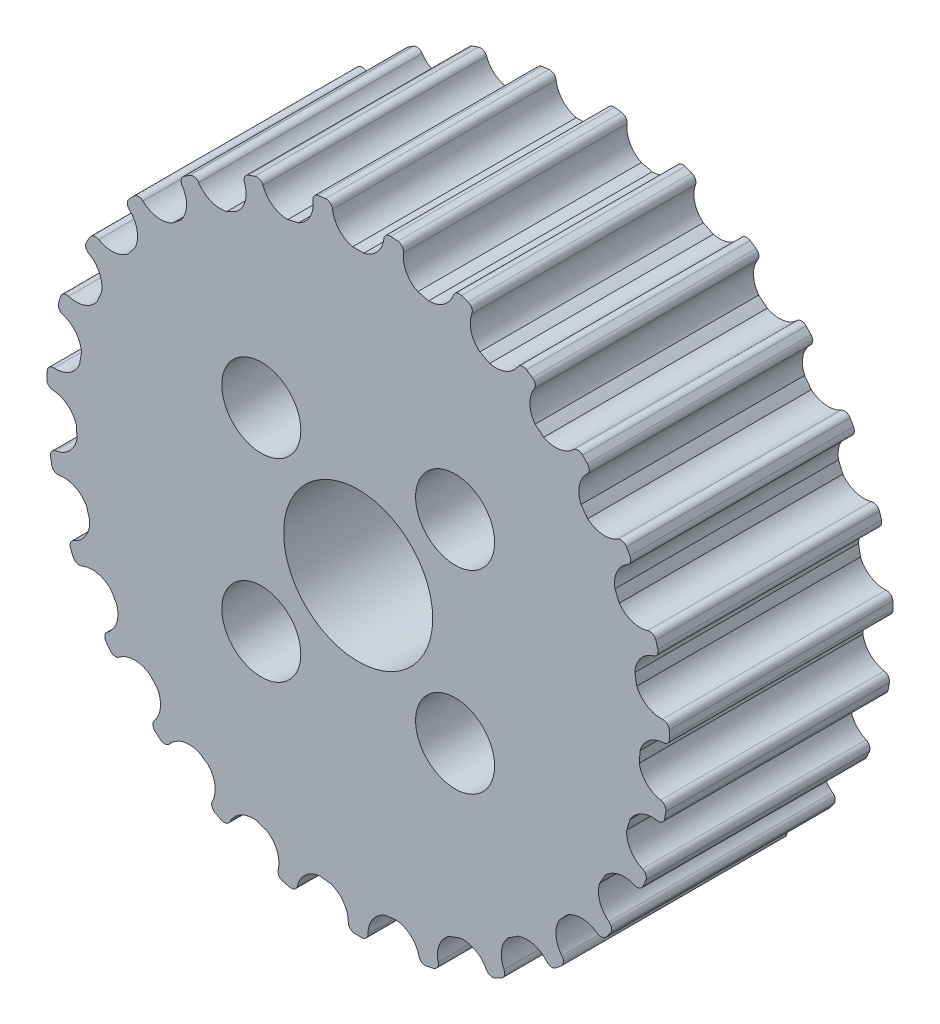
SolidWorks part; units mm, degrees
ref_plane "Front Plane" through (0, 0, 0) normal (0, 0, 1) x (1, 0, 0)
ref_plane "Top Plane" through (0, 0, 0) normal (0, 1, 0) x (1, 0, 0)
ref_plane "Right Plane" through (0, 0, 0) normal (1, 0, 0) x (0, 0, -1)
ref_plane "Plane1" through (0, 0, 7.5) normal (0, 0, 1) x (1, 0, 0)
sketch "Sketch1" plane through (0, 0, 7.5) normal (0, 0, 1) x (1, 0, 0)
  arc A0 (-2.1927, 20.7989) -> (-2.663, 20.7439) centre (0, 0) ccw
  arc A1 (-2.663, 20.7439) -> (-3.0351, 20.266) centre (-2.6082, 20.3174) ccw
  arc A2 (-3.0351, 20.266) -> (-3.9982, 18.4886) centre (-4.7708, 20.0568) cw
  arc A3 (-3.9982, 18.4886) -> (-4.7247, 18.3164) centre (0, 0) ccw
  arc A4 (-4.7247, 18.3164) -> (-6.3831, 19.4725) centre (-4.7381, 20.0646) cw
  arc A5 (-6.3831, 19.4725) -> (-6.9301, 19.7326) centre (-6.7876, 19.3269) ccw
  arc A6 (-6.9301, 19.7326) -> (-7.3751, 19.5706) centre (0, 0) ccw
  arc A7 (-7.3751, 19.5706) -> (-7.627, 19.0198) centre (-7.2234, 19.1683) ccw
  arc A8 (-7.627, 19.0198) -> (-8.1542, 17.0682) centre (-9.2676, 18.416) cw
  arc A9 (-8.1542, 17.0682) -> (-8.8214, 16.7331) centre (0, 0) ccw
  arc A10 (-8.8214, 16.7331) -> (-10.7017, 17.4756) centre (-9.2376, 18.431) cw
  arc A11 (-10.7017, 17.4756) -> (-11.294, 17.6025) centre (-11.0618, 17.2406) ccw
  arc A12 (-11.294, 17.6025) -> (-11.6896, 17.3423) centre (0, 0) ccw
  arc A13 (-11.6896, 17.3423) -> (-11.8077, 16.7482) centre (-11.4492, 16.9857) ccw
  arc A14 (-11.8077, 16.7482) -> (-11.8706, 14.7276) centre (-13.2649, 15.7823) cw
  arc A15 (-11.8706, 14.7276) -> (-12.4425, 14.2477) centre (0, 0) ccw
  arc A16 (-12.4425, 14.2477) -> (-14.4433, 14.5366) centre (-13.2391, 15.8039) cw
  arc A17 (-14.4433, 14.5366) -> (-15.049, 14.5235) centre (-14.7395, 14.2248) ccw
  arc A18 (-15.049, 14.5235) -> (-15.3739, 14.179) centre (0, 0) ccw
  arc A19 (-15.3739, 14.179) -> (-15.3518, 13.5737) centre (-15.0578, 13.8875) ccw
  arc A20 (-15.3518, 13.5737) -> (-14.947, 11.5931) centre (-16.5469, 12.2978) cw
  arc A21 (-14.947, 11.5931) -> (-15.3929, 10.9942) centre (0, 0) ccw
  arc A22 (-15.3929, 10.9942) -> (-17.4064, 10.8139) centre (-16.5269, 12.3248) cw
  arc A23 (-17.4064, 10.8139) -> (-17.9926, 10.6614) centre (-17.6227, 10.4422) ccw
  arc A24 (-17.9926, 10.6614) -> (-18.2294, 10.2514) centre (0, 0) ccw
  arc A25 (-18.2294, 10.2514) -> (-18.0683, 9.6674) centre (-17.8546, 10.0406) ccw
  arc A26 (-18.0683, 9.6674) -> (-17.2177, 7.8335) centre (-18.937, 8.1503) cw
  arc A27 (-17.2177, 7.8335) -> (-17.5134, 7.148) centre (0, 0) ccw
  arc A28 (-17.5134, 7.148) -> (-19.431, 6.5082) centre (-18.9237, 8.1812) cw
  arc A29 (-19.431, 6.5082) -> (-19.9664, 6.2247) centre (-19.5558, 6.0967) ccw
  arc A30 (-19.9664, 6.2247) -> (-20.1022, 5.7711) centre (0, 0) ccw
  arc A31 (-20.1022, 5.7711) -> (-19.8107, 5.24) centre (-19.6889, 5.6524) ccw
  arc A32 (-19.8107, 5.24) -> (-18.5601, 3.6517) centre (-20.3061, 3.5635) cw
  arc A33 (-18.5601, 3.6517) -> (-18.6898, 2.9164) centre (0, 0) ccw
  arc A34 (-18.6898, 2.9164) -> (-20.4082, 1.8516) centre (-20.3003, 3.5966) cw
  arc A35 (-20.4082, 1.8516) -> (-20.8637, 1.4523) centre (-20.4347, 1.4225) ccw
  arc A36 (-20.8637, 1.4523) -> (-20.8912, 0.9796) centre (0, 0) ccw
  arc A37 (-20.8912, 0.9796) -> (-20.4851, 0.5301) centre (-20.4617, 0.9595) ccw
  arc A38 (-20.4851, 0.5301) -> (-18.902, -0.727) centre (-20.5806, -1.2155) cw
  arc A39 (-18.902, -0.727) -> (-18.8586, -1.4723) centre (0, 0) ccw
  arc A40 (-18.8586, -1.4723) -> (-20.2851, -2.9047) centre (-20.5825, -1.182) cw
  arc A41 (-20.2851, -2.9047) -> (-20.6362, -3.3983) centre (-20.2119, -3.3284) ccw
  arc A42 (-20.6362, -3.3983) -> (-20.554, -3.8646) centre (0, 0) ccw
  arc A43 (-20.554, -3.8646) -> (-20.0552, -4.2084) centre (-20.1314, -3.7852) ccw
  arc A44 (-20.0552, -4.2084) -> (-18.2248, -5.0665) centre (-19.7455, -5.929) cw
  arc A45 (-18.2248, -5.0665) -> (-18.0107, -5.7817) centre (0, 0) ccw
  arc A46 (-18.0107, -5.7817) -> (-19.0684, -7.5045) centre (-19.7551, -5.8968) cw
  arc A47 (-19.0684, -7.5045) -> (-19.2963, -8.0657) centre (-18.8995, -7.8999) ccw
  arc A48 (-19.2963, -8.0657) -> (-19.1087, -8.5005) centre (0, 0) ccw
  arc A49 (-19.1087, -8.5005) -> (-18.5441, -8.72) centre (-18.7158, -8.3258) ccw
  arc A50 (-18.5441, -8.72) -> (-16.5652, -9.1328) centre (-17.8459, -10.3228) cw
  arc A51 (-16.5652, -9.1328) -> (-16.1918, -9.7794) centre (0, 0) ccw
  arc A52 (-16.1918, -9.7794) -> (-16.8238, -11.6997) centre (-17.8627, -10.2937) cw
  arc A53 (-16.8238, -11.6997) -> (-16.916, -12.2984) centre (-16.5682, -12.0455) ccw
  arc A54 (-16.916, -12.2984) -> (-16.6333, -12.6782) centre (0, 0) ccw
  arc A55 (-16.6333, -12.6782) -> (-16.0333, -12.7615) centre (-16.2913, -12.4175) ccw
  arc A56 (-16.0333, -12.7615) -> (-14.0125, -12.7068) centre (-14.9843, -14.1601) cw
  arc A57 (-14.0125, -12.7068) -> (-13.5001, -13.2499) centre (0, 0) ccw
  arc A58 (-13.5001, -13.2499) -> (-13.6722, -15.2641) centre (-15.0074, -14.1356) cw
  arc A59 (-13.6722, -15.2641) -> (-13.6239, -15.868) centre (-13.3438, -15.5417) ccw
  arc A60 (-13.6239, -15.868) -> (-13.2611, -16.1723) centre (0, 0) ccw
  arc A61 (-13.2611, -16.1723) -> (-12.6581, -16.115) centre (-12.9885, -15.8398) ccw
  arc A62 (-12.6581, -16.115) -> (-10.7044, -15.5958) centre (-11.3149, -17.234) cw
  arc A63 (-10.7044, -15.5958) -> (-10.0806, -16.0061) centre (0, 0) ccw
  arc A64 (-10.0806, -16.0061) -> (-9.7835, -18.0057) centre (-11.3429, -17.2155) cw
  arc A65 (-9.7835, -18.0057) -> (-9.5972, -18.5821) centre (-9.3999, -18.2001) ccw
  arc A66 (-9.5972, -18.5821) -> (-9.1741, -18.7946) centre (0, 0) ccw
  arc A67 (-9.1741, -18.7946) -> (-8.6005, -18.5998) centre (-8.9855, -18.4082) ccw
  arc A68 (-8.6005, -18.5998) -> (-6.8192, -17.644) centre (-7.0354, -19.3788) cw
  arc A69 (-6.8192, -17.644) -> (-6.1176, -17.8994) centre (0, 0) ccw
  arc A70 (-6.1176, -17.8994) -> (-5.3674, -19.7766) centre (-7.067, -19.3674) cw
  arc A71 (-5.3674, -19.7766) -> (-5.0532, -20.2945) centre (-4.9493, -19.8772) ccw
  arc A72 (-5.0532, -20.2945) -> (-4.5925, -20.4037) centre (0, 0) ccw
  arc A73 (-4.5925, -20.4037) -> (-4.0793, -20.0819) centre (-4.498, -19.9842) ccw
  arc A74 (-4.0793, -20.0819) -> (-2.5664, -18.7411) centre (-2.3767, -20.479) cw
  arc A75 (-2.5664, -18.7411) -> (-1.8248, -18.8277) centre (0, 0) ccw
  arc A76 (-1.8248, -18.8277) -> (-0.6619, -20.4813) centre (-2.4101, -20.4751) cw
  arc A77 (-0.6619, -20.4813) -> (-0.2368, -20.9128) centre (-0.2319, -20.4828) ccw
  arc A78 (-0.2368, -20.9128) -> (0.2368, -20.9128) centre (0, 0) ccw
  arc A79 (0.2368, -20.9128) -> (0.6619, -20.4813) centre (0.2319, -20.4828) ccw
  arc A80 (0.6619, -20.4813) -> (1.8248, -18.8277) centre (2.4101, -20.4751) cw
  arc A81 (1.8248, -18.8277) -> (2.5664, -18.7411) centre (0, 0) ccw
  arc A82 (2.5664, -18.7411) -> (4.0793, -20.0819) centre (2.3767, -20.479) cw
  arc A83 (4.0793, -20.0819) -> (4.5925, -20.4037) centre (4.498, -19.9842) ccw
  arc A84 (4.5925, -20.4037) -> (5.0532, -20.2945) centre (0, 0) ccw
  arc A85 (5.0532, -20.2945) -> (5.3674, -19.7766) centre (4.9493, -19.8772) ccw
  arc A86 (5.3674, -19.7766) -> (6.1176, -17.8994) centre (7.067, -19.3674) cw
  arc A87 (6.1176, -17.8994) -> (6.8192, -17.644) centre (0, 0) ccw
  arc A88 (6.8192, -17.644) -> (8.6005, -18.5998) centre (7.0354, -19.3788) cw
  arc A89 (8.6005, -18.5998) -> (9.1741, -18.7946) centre (8.9855, -18.4082) ccw
  arc A90 (9.1741, -18.7946) -> (9.5972, -18.5821) centre (0, 0) ccw
  arc A91 (9.5972, -18.5821) -> (9.7835, -18.0057) centre (9.3999, -18.2001) ccw
  arc A92 (9.7835, -18.0057) -> (10.0806, -16.0061) centre (11.3429, -17.2155) cw
  arc A93 (10.0806, -16.0061) -> (10.7044, -15.5958) centre (0, 0) ccw
  arc A94 (10.7044, -15.5958) -> (12.6581, -16.115) centre (11.3149, -17.234) cw
  arc A95 (12.6581, -16.115) -> (13.2611, -16.1723) centre (12.9885, -15.8398) ccw
  arc A96 (13.2611, -16.1723) -> (13.6239, -15.868) centre (0, 0) ccw
  arc A97 (13.6239, -15.868) -> (13.6722, -15.2641) centre (13.3438, -15.5417) ccw
  arc A98 (13.6722, -15.2641) -> (13.5001, -13.2499) centre (15.0074, -14.1356) cw
  arc A99 (13.5001, -13.2499) -> (14.0125, -12.7068) centre (0, 0) ccw
  arc A100 (14.0125, -12.7068) -> (16.0333, -12.7615) centre (14.9843, -14.1601) cw
  arc A101 (16.0333, -12.7615) -> (16.6333, -12.6782) centre (16.2913, -12.4175) ccw
  arc A102 (16.6333, -12.6782) -> (16.916, -12.2984) centre (0, 0) ccw
  arc A103 (16.916, -12.2984) -> (16.8238, -11.6997) centre (16.5682, -12.0455) ccw
  arc A104 (16.8238, -11.6997) -> (16.1918, -9.7794) centre (17.8627, -10.2937) cw
  arc A105 (16.1918, -9.7794) -> (16.5652, -9.1328) centre (0, 0) ccw
  arc A106 (16.5652, -9.1328) -> (18.5441, -8.72) centre (17.8459, -10.3228) cw
  arc A107 (18.5441, -8.72) -> (19.1087, -8.5005) centre (18.7158, -8.3258) ccw
  arc A108 (19.1087, -8.5005) -> (19.2963, -8.0657) centre (0, 0) ccw
  arc A109 (19.2963, -8.0657) -> (19.0684, -7.5045) centre (18.8995, -7.8999) ccw
  arc A110 (19.0684, -7.5045) -> (18.0107, -5.7817) centre (19.7551, -5.8968) cw
  arc A111 (18.0107, -5.7817) -> (18.2248, -5.0665) centre (0, 0) ccw
  arc A112 (18.2248, -5.0665) -> (20.0552, -4.2084) centre (19.7455, -5.929) cw
  arc A113 (20.0552, -4.2084) -> (20.554, -3.8646) centre (20.1314, -3.7852) ccw
  arc A114 (20.554, -3.8646) -> (20.6362, -3.3983) centre (0, 0) ccw
  arc A115 (20.6362, -3.3983) -> (20.2851, -2.9047) centre (20.2119, -3.3284) ccw
  arc A116 (20.2851, -2.9047) -> (18.8586, -1.4723) centre (20.5825, -1.182) cw
  arc A117 (18.8586, -1.4723) -> (18.902, -0.727) centre (0, 0) ccw
  arc A118 (18.902, -0.727) -> (20.4851, 0.5301) centre (20.5806, -1.2155) cw
  arc A119 (20.4851, 0.5301) -> (20.8912, 0.9796) centre (20.4617, 0.9595) ccw
  arc A120 (20.8912, 0.9796) -> (20.8637, 1.4523) centre (0, 0) ccw
  arc A121 (20.8637, 1.4523) -> (20.4082, 1.8516) centre (20.4347, 1.4225) ccw
  arc A122 (20.4082, 1.8516) -> (18.6898, 2.9164) centre (20.3003, 3.5966) cw
  arc A123 (18.6898, 2.9164) -> (18.5601, 3.6517) centre (0, 0) ccw
  arc A124 (18.5601, 3.6517) -> (19.8107, 5.24) centre (20.3061, 3.5635) cw
  arc A125 (19.8107, 5.24) -> (20.1022, 5.7711) centre (19.6889, 5.6524) ccw
  arc A126 (20.1022, 5.7711) -> (19.9664, 6.2247) centre (0, 0) ccw
  arc A127 (19.9664, 6.2247) -> (19.431, 6.5082) centre (19.5558, 6.0967) ccw
  arc A128 (19.431, 6.5082) -> (17.5134, 7.148) centre (18.9237, 8.1812) cw
  arc A129 (17.5134, 7.148) -> (17.2177, 7.8335) centre (0, 0) ccw
  arc A130 (17.2177, 7.8335) -> (18.0683, 9.6674) centre (18.937, 8.1503) cw
  arc A131 (18.0683, 9.6674) -> (18.2294, 10.2514) centre (17.8546, 10.0406) ccw
  arc A132 (18.2294, 10.2514) -> (17.9926, 10.6614) centre (0, 0) ccw
  arc A133 (17.9926, 10.6614) -> (17.4064, 10.8139) centre (17.6227, 10.4422) ccw
  arc A134 (17.4064, 10.8139) -> (15.3929, 10.9942) centre (16.5269, 12.3248) cw
  arc A135 (15.3929, 10.9942) -> (14.947, 11.5931) centre (0, 0) ccw
  arc A136 (14.947, 11.5931) -> (15.3518, 13.5737) centre (16.5469, 12.2978) cw
  arc A137 (15.3518, 13.5737) -> (15.3739, 14.179) centre (15.0578, 13.8875) ccw
  arc A138 (15.3739, 14.179) -> (15.049, 14.5235) centre (0, 0) ccw
  arc A139 (15.049, 14.5235) -> (14.4433, 14.5366) centre (14.7395, 14.2248) ccw
  arc A140 (14.4433, 14.5366) -> (12.4425, 14.2477) centre (13.2391, 15.8039) cw
  arc A141 (12.4425, 14.2477) -> (11.8706, 14.7276) centre (0, 0) ccw
  arc A142 (11.8706, 14.7276) -> (11.8077, 16.7482) centre (13.2649, 15.7823) cw
  arc A143 (11.8077, 16.7482) -> (11.6896, 17.3423) centre (11.4492, 16.9857) ccw
  arc A144 (11.6896, 17.3423) -> (11.294, 17.6025) centre (0, 0) ccw
  arc A145 (11.294, 17.6025) -> (10.7017, 17.4756) centre (11.0618, 17.2406) ccw
  arc A146 (10.7017, 17.4756) -> (8.8214, 16.7331) centre (9.2376, 18.431) cw
  arc A147 (8.8214, 16.7331) -> (8.1542, 17.0682) centre (0, 0) ccw
  arc A148 (8.1542, 17.0682) -> (7.627, 19.0198) centre (9.2676, 18.416) cw
  arc A149 (7.627, 19.0198) -> (7.3751, 19.5706) centre (7.2234, 19.1683) ccw
  arc A150 (7.3751, 19.5706) -> (6.9301, 19.7326) centre (0, 0) ccw
  arc A151 (6.9301, 19.7326) -> (6.3831, 19.4725) centre (6.7876, 19.3269) ccw
  arc A152 (6.3831, 19.4725) -> (4.7247, 18.3164) centre (4.7381, 20.0646) cw
  arc A153 (4.7247, 18.3164) -> (3.9982, 18.4886) centre (0, 0) ccw
  arc A154 (3.9982, 18.4886) -> (3.0351, 20.266) centre (4.7708, 20.0568) cw
  arc A155 (3.0351, 20.266) -> (2.663, 20.7439) centre (2.6082, 20.3174) ccw
  arc A156 (2.663, 20.7439) -> (2.1927, 20.7989) centre (0, 0) ccw
  arc A157 (2.1927, 20.7989) -> (1.7203, 20.4197) centre (2.1476, 20.3713) ccw
  arc A158 (1.7203, 20.4197) -> (0.3733, 18.9123) centre (-0.0168, 20.6164) cw
  arc A159 (0.3733, 18.9123) -> (-0.3733, 18.9123) centre (0, 0) ccw
  arc A160 (-0.3733, 18.9123) -> (-1.7203, 20.4197) centre (0.0168, 20.6164) cw
  arc A161 (-1.7203, 20.4197) -> (-2.1927, 20.7989) centre (-2.1476, 20.3713) ccw
extrude "Boss-Extrude1" add sketch "Sketch1" against normal blind 15
sketch "Sketch2" plane through (0, 0, 7.5) normal (0, 0, 1) x (1, 0, 0)
  line L1 (-6.5, -6.5) -> (6.5, -6.5) construction
  line L2 (-6.5, -6.5) -> (-6.5, 6.5) construction
  line L3 (-6.5, 6.5) -> (6.5, 6.5) construction
  line L4 (6.5, -6.5) -> (6.5, 6.5) construction
  line L5 (-6.5, -6.5) -> (6.5, 6.5) construction
  line L6 (-6.5, 6.5) -> (6.5, -6.5) construction
  circle A1 centre (-6.5, 6.5) radius 2.65
  circle A2 centre (6.5, 6.5) radius 2.65
  circle A3 centre (6.5, -6.5) radius 2.65
  circle A4 centre (-6.5, -6.5) radius 2.65
  circle A5 centre (0, 0) radius 5
  point P0 (0, 0)
  dimension "D2" = 13
  dimension "D3" = 5.3
  dimension "D4" = 5.3
  dimension "D5" = 5.3
  dimension "D6" = 5.3
  dimension "D7" = 10
  dimension "D1" = 13
extrude "Cut-Extrude1" cut sketch "Sketch2" against normal through all
